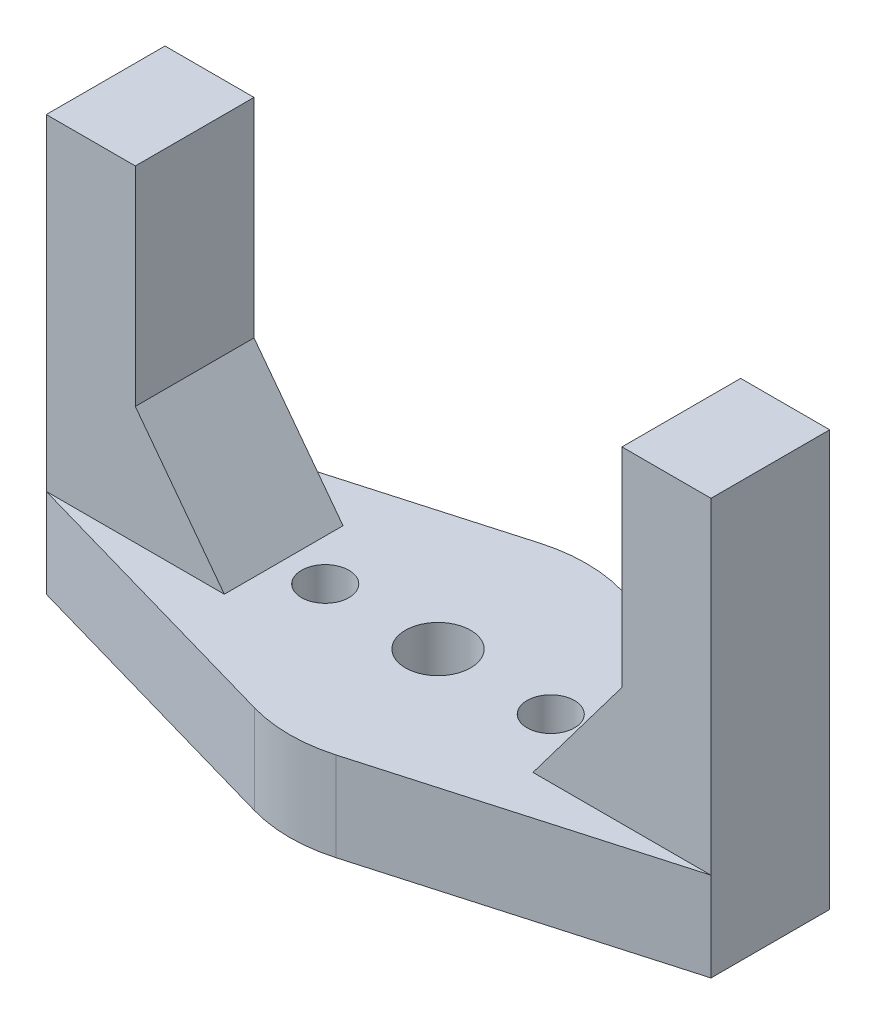
SolidWorks part; units mm, degrees
ref_plane "Front Plane" through (0, 0, 0) normal (0, 0, 1) x (1, 0, 0)
ref_plane "Top Plane" through (0, 0, 0) normal (0, 1, 0) x (1, 0, 0)
ref_plane "Right Plane" through (0, 0, 0) normal (1, 0, 0) x (0, 0, -1)
sketch "Sketch1" plane through (0, 0, 0) normal (0, 1, 0) x (1, 0, 0)
  line L1 (-29, -29) -> (29, -29) construction
  line L2 (-29, -29) -> (-29, 29) construction
  line L3 (-29, 29) -> (29, 29) construction
  line L4 (29, -29) -> (29, 29) construction
  line L5 (0, 29) -> (0, -29) construction
  line L6 (-29, 0) -> (29, 0) construction
  circle A0 centre (-19, 0) radius 1.8
  circle A1 centre (19, 0) radius 1.8
  circle A4 centre (0, 0) radius 5.5
  circle A5 centre (0, 0) radius 25
  point P0 (0, 0)
  dimension "D3" = 3.6
  dimension "D5" = 10
  dimension "D6" = 11
  dimension "D2" = 50
  dimension "D1" = 58
extrude "Boss-Extrude1" add sketch "Sketch1" along normal blind 15
sketch "Sketch2" plane through (0, 15, 0) normal (0, 1, 0) x (1, 0, 0)
  circle A4 centre (-19, 0) radius 4
  circle A5 centre (19, 0) radius 4
  dimension "D1" = 8
  dimension "D2" = 8
extrude "Cut-Extrude1" cut sketch "Sketch2" against normal blind 8
sketch "Sketch3" plane through (0, 0, 0) normal (0, -1, 0) x (1, 0, 0)
  line L1 (-41, -25) -> (41, -25)
  line L2 (-41, -25) -> (-41, 25)
  line L3 (-41, 25) -> (41, 25)
  line L4 (41, -25) -> (41, 25)
  line L5 (-41, -25) -> (41, 25) construction
  line L6 (-41, 25) -> (41, -25) construction
  circle A0 centre (0, 0) radius 25 construction
  circle A2 centre (0, 0) radius 24.5
  dimension "D2" = 49
  dimension "D1" = 82
extrude "Boss-Extrude2" add sketch "Sketch3" against normal up to surface (15 mm away) up to face at (-19, 15, 4)
sketch "Sketch4" plane through (0, 0, 0) normal (0, -1, 0) x (1, 0, 0)
  line L0 (0, -999.6046) -> (0, 49000.3954) construction
  line L6 (-41, 25) -> (-41, -25) construction
  line L7 (-56, -10) -> (-41, -10)
  line L8 (-56, -10) -> (-56, 10)
  line L9 (-56, 10) -> (-41, 10)
  line L14 (-41, -10) -> (-41, 10)
  line L15 (-56, -10) -> (-41, 10) construction
  line L16 (-56, 10) -> (-41, -10) construction
  line L17 (56, 10) -> (41, -10) construction
  line L18 (56, -10) -> (41, 10) construction
  line L19 (41, -10) -> (41, 10)
  line L20 (56, 10) -> (41, 10)
  line L21 (56, -10) -> (56, 10)
  line L22 (56, -10) -> (41, -10)
  point P1 (-48.5, 0)
  point P8 (-53.7999, 6.7347)
  point P15 (48.5, 0)
  dimension "D1" = 15
  dimension "D2" = 20
extrude "Boss-Extrude3" add sketch "Sketch4" against normal blind 70
sketch "Sketch5" plane through (0, 0, 0) normal (0, -1, 0) x (1, 0, 0)
  line L0 (0, -1000) -> (0, 49000) construction
  line L1 (-56, 10) -> (-6.8682, 24.038)
  line L3 (-56, 10) -> (-56, 25)
  line L4 (-56, 25) -> (56, 25)
  line L7 (56, 10) -> (56, 25)
  line L8 (56, 10) -> (6.8682, 24.038)
  line L9 (-1000, 0) -> (49000, 0) construction
  line L10 (56, -10) -> (56, -25)
  line L11 (56, -10) -> (6.8682, -24.038)
  line L12 (0, 1000) -> (0, -49000) construction
  line L13 (-56, -25) -> (56, -25)
  line L14 (-56, -10) -> (-56, -25)
  line L15 (-56, -10) -> (-6.8682, -24.038)
  circle A1 centre (0, 0) radius 25
  point P12 (0, 25)
  point P24 (0, -25)
  line M9 (-41, 25) -> (-41, 10)
  line M13 (-41, -10) -> (-41, -25)
  line M14 (-41, -25) -> (41, -25)
  line M15 (41, -25) -> (41, -10)
  line M19 (41, 10) -> (41, 25)
  line M20 (41, 25) -> (-41, 25)
  dimension "D1" = 50
extrude "Cut-Extrude2" cut sketch "Sketch5" against normal through all both and the other way through all contours L15 L14 L13 M13 | A1 L15 M13 M14 | L4 L3 L1 M9 | A1 L4 L1 M9 | A1 L8 M19 M20 | A1 L13 L11 M15 | L13 L10 L11 M15 | L8 L7 L4 M19
sketch "Sketch6" plane through (0, 0, 0) normal (0, -1, 0) x (1, 0, 0)
  line L0 (-56, 10) -> (-41, 14.2858)
  line L1 (-41, 14.2858) -> (-41, -14.2858)
  line L2 (-41, -14.2858) -> (-56, -10)
  line L3 (-56, -10) -> (-56, 10)
  line L4 (41, 14.2858) -> (56, 10)
  line L5 (56, 10) -> (56, -10)
  line L6 (56, -10) -> (41, -14.2858)
  line L7 (41, -14.2858) -> (41, 14.2858)
extrude "Boss-Extrude4" add sketch "Sketch6" against normal up to surface (15 mm away) up to face at (0, 15, 5.5)
chamfer "Chamfer1" distance 15 angle 53 2 edges at (41, 15, 0) (-41, 15, 0)
